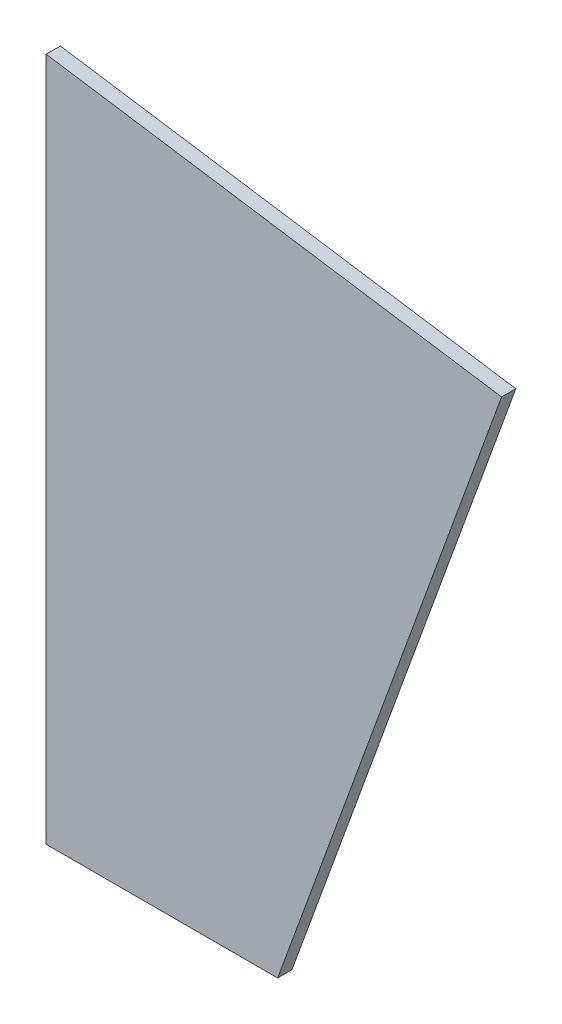
SolidWorks part; units mm, degrees
ref_plane "Front Plane" through (0, 0, 0) normal (0, 0, 1) x (1, 0, 0)
ref_plane "Top Plane" through (0, 0, 0) normal (0, 1, 0) x (1, 0, 0)
ref_plane "Right Plane" through (0, 0, 0) normal (1, 0, 0) x (0, 0, -1)
sketch "Sketch1" plane through (0, 0, 0) normal (0, 0, 1) x (1, 0, 0)
  line L0 (0, 0) -> (0, 152.4)
  line L1 (0, 0) -> (51.562, 0)
  line L2 (51.562, 0) -> (101.4272, 137.0034)
  line L3 (101.4272, 137.0034) -> (0, 152.4)
  dimension "D1" = 152.4
  dimension "D2" = 51.562
  dimension "D3" = 145.796
  dimension "D4" = 110
extrude "Boss-Extrude1" add sketch "Sketch1" along normal blind 3.175
